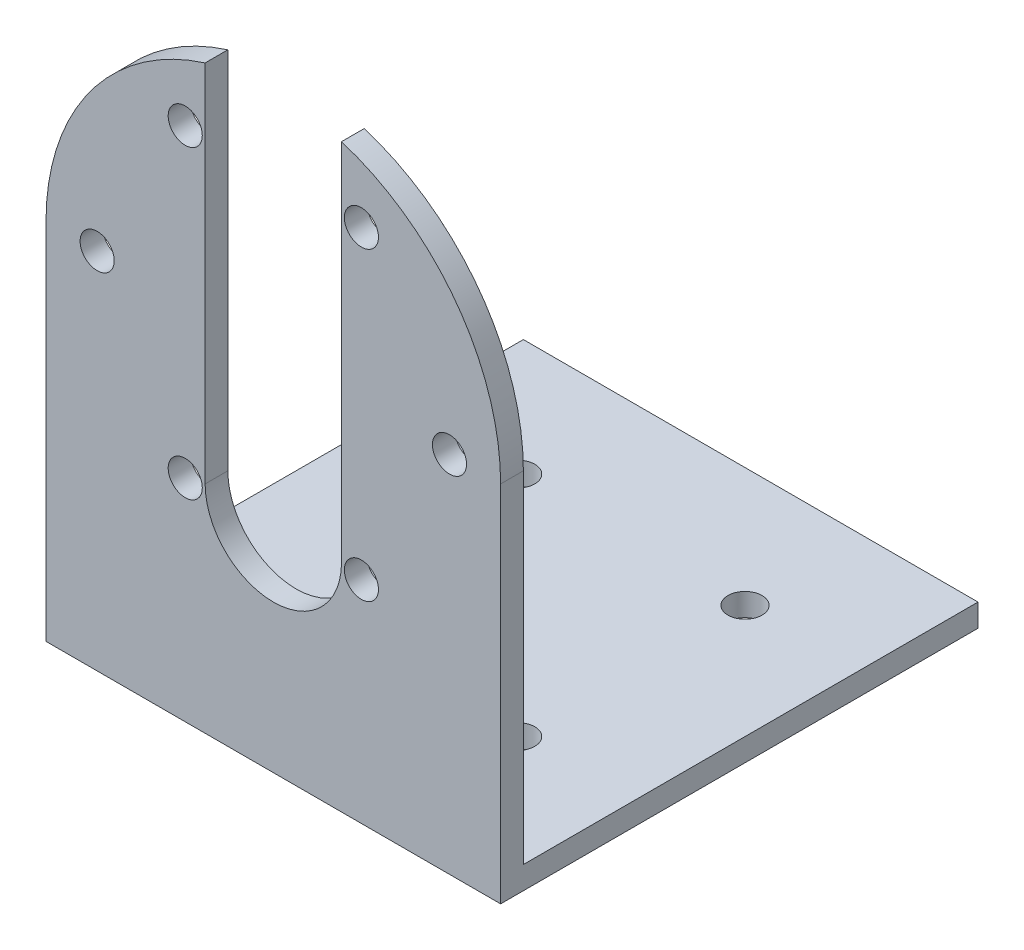
SolidWorks part; units mm, degrees
ref_plane "Front Plane" through (0, 0, 0) normal (0, 0, 1) x (1, 0, 0)
ref_plane "Top Plane" through (0, 0, 0) normal (0, 1, 0) x (1, 0, 0)
ref_plane "Right Plane" through (0, 0, 0) normal (1, 0, 0) x (0, 0, -1)
sketch "Sketch1" plane through (0, 0, 0) normal (0, 1, 0) x (1, 0, 0)
  line L1 (-20, 21) -> (20, 21)
  line L2 (-20, 21) -> (-20, -21)
  line L3 (-20, -21) -> (20, -21)
  line L4 (20, 21) -> (20, -21)
  line L5 (-20, 21) -> (20, -21) construction
  line L6 (-20, -21) -> (20, 21) construction
  point P0 (0, 0)
  dimension "D1" = 40
  dimension "D2" = 42
extrude "Boss-Extrude1" add sketch "Sketch1" along normal blind 2
sketch "Sketch2" plane through (0, 2, 0) normal (0, 1, 0) x (1, 0, 0)
  line L0 (-20, -21) -> (-20, -19)
  line L1 (-20, 21) -> (-20, -21) construction
  line L2 (-20, -19) -> (20, -19)
  line L3 (20, -21) -> (20, 21) construction
  line L4 (20, -19) -> (20, -21)
  line L5 (20, -21) -> (-20, -21)
  dimension "D1" = 2
extrude "Boss-Extrude2" add sketch "Sketch2" along normal blind 50
sketch "Sketch3" plane through (0, 0, 21) normal (0, 0, 1) x (1, 0, 0)
  line L0 (-20, 32) -> (-20, 52)
  line L1 (-20, 52) -> (20, 52)
  line L2 (20, 52) -> (20, 32)
  arc A0 (20, 32) -> (-20, 32) centre (0, 32) ccw
  line M3 (20, 0) -> (20, 52)
  line M4 (20, 52) -> (-20, 52)
  line M5 (-20, 52) -> (-20, 0)
extrude "Cut-Extrude1" cut sketch "Sketch3" against normal blind 50 contours A0 L1 M5 | A0 M3 M4
sketch "Sketch4" plane through (0, 0, 21) normal (0, 0, 1) x (1, 0, 0)
  line L0 (-20, 32) -> (20, 32)
  circle A0 centre (0, 32) radius 15.5
  circle A1 centre (-15.5, 32) radius 1.5
  circle A2 centre (15.5, 32) radius 1.5
  circle A3 centre (7.75, 18.5766) radius 1.5
  circle A4 centre (-7.75, 18.5766) radius 1.5
  circle A5 centre (-15.5, 32) radius 1.5
  circle A6 centre (-7.75, 45.4234) radius 1.5
  circle A7 centre (7.75, 45.4234) radius 1.5
  point P23 (0, 32)
  dimension "D1" = 31
  dimension "D2" = 6
extrude "Cut-Extrude2" cut sketch "Sketch4" against normal blind 50 contours A1 | A4 | A6 | A7 | A2 | A3
sketch "Sketch5" plane through (0, 0, 21) normal (0, 0, 1) x (1, 0, 0)
  line L0 (0, 52) -> (0, 19)
  line L1 (-6, 19) -> (-6, 51.0788)
  line L2 (6, 19) -> (6, 51.0788)
  arc A0 (20, 32) -> (-20, 32) centre (0, 32) ccw construction
  circle A1 centre (0, 19) radius 6
  arc A2 (-6, 51.0788) -> (6, 51.0788) centre (0, 32) cw
  dimension "D1" = 12
  dimension "D2" = 33
extrude "Cut-Extrude3" cut sketch "Sketch5" against normal blind 1033
sketch "Sketch6" plane through (0, 0, 0) normal (0, -1, 0) x (1, 0, 0)
  line L0 (10, -10.5) -> (10, 9.5)
  line L2 (20, -21) -> (-20, -21)
  circle A2 centre (-10, -10.5) radius 1.5
  circle A3 centre (10, -10.5) radius 1.5
  circle A4 centre (10, 9.5) radius 1.5
  circle A5 centre (-10, 9.5) radius 1.5
  point P1 (0, 0)
  dimension "D1" = 20
  dimension "D2" = 20
  dimension "D3" = 20
  dimension "D4" = 10
  dimension "D6" = 20
extrude "Cut-Extrude4" cut sketch "Sketch6" against normal blind 1033 contours A5 | A4 | A3 | A2
